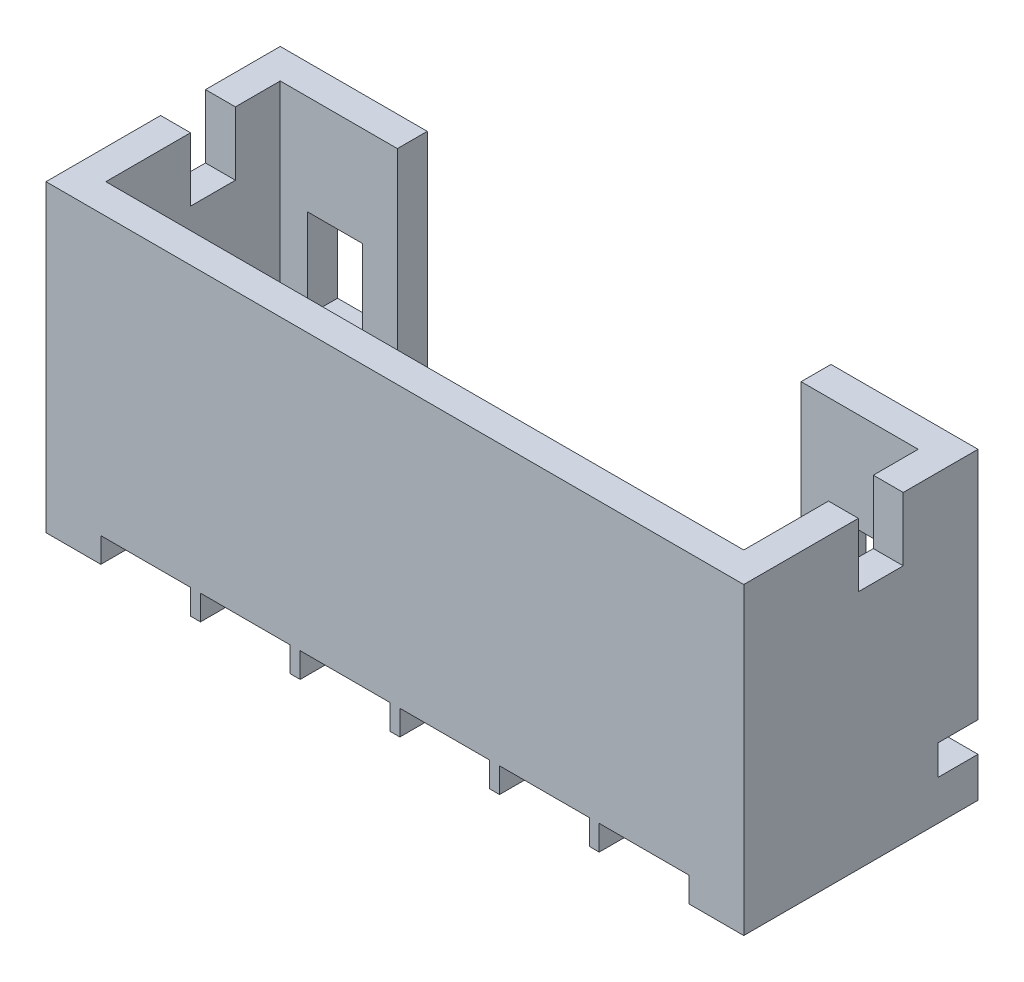
SolidWorks part; units mm, degrees
material "ABS"
ref_plane "Plano frontal" through (0, 0, 0) normal (0, 0, 1) x (1, 0, 0)
ref_plane "Plano superior" through (0, 0, 0) normal (0, 1, 0) x (1, 0, 0)
ref_plane "Plano direito" through (0, 0, 0) normal (1, 0, 0) x (0, 0, -1)
sketch "Esboço1" plane through (0, 0, 0) normal (0, 1, 0) x (1, 0, 0)
  line L1 (-7, -2.35) -> (7, -2.35)
  line L2 (-7, -2.35) -> (-7, 2.35)
  line L3 (-7, 2.35) -> (7, 2.35)
  line L4 (7, -2.35) -> (7, 2.35)
  line L5 (-7, -2.35) -> (7, 2.35) construction
  line L6 (-7, 2.35) -> (7, -2.35) construction
  point P0 (0, 0)
  dimension "D1" = 4.7
  dimension "D2" = 14
extrude "Ressalto-extrusão1" add sketch "Esboço1" along normal mid plane 6.1
shell "Casca1" thickness 0.6
sketch "Esboço2" plane through (0, 0, -2.35) normal (0, 0, -1) x (-1, 0, 0)
  line L0 (-4.05, 3.05) -> (-4.05, -1.35)
  line L1 (-7, 3.05) -> (7, 3.05) construction
  line L2 (-4.05, -1.35) -> (4.05, -1.35)
  line L3 (4.05, -1.35) -> (4.05, 3.05)
  line L4 (0, 0) -> (0, 2.0784) construction
  line L5 (0, 0) -> (1.8977, 0) construction
  line L7 (4.75, -0.75) -> (5.85, -0.75)
  line L8 (4.75, -0.75) -> (4.75, 1.05)
  line L9 (4.75, 1.05) -> (5.85, 1.05)
  line L10 (5.85, -0.75) -> (5.85, 1.05)
  line L11 (4.75, -0.75) -> (5.85, 1.05) construction
  line L12 (4.75, 1.05) -> (5.85, -0.75) construction
  line L13 (-5.85, 1.05) -> (-4.75, 1.05)
  line L14 (-5.85, 1.05) -> (-5.85, -0.75)
  line L15 (-5.85, -0.75) -> (-4.75, -0.75)
  line L16 (-4.75, 1.05) -> (-4.75, -0.75)
  line L17 (-5.85, 1.05) -> (-4.75, -0.75) construction
  line L18 (-5.85, -0.75) -> (-4.75, 1.05) construction
  line L19 (-7, 3.05) -> (-7, -3.05) construction
  line L20 (-4.05, 3.05) -> (4.05, 3.05)
  point P4 (0, -1.35)
  point P8 (5.3, 0.15)
  point P14 (-5.3, 0.15)
  dimension "D1" = 8.1
  dimension "D2" = 4.4
  dimension "D3" = 1.1
  dimension "D4" = 1.8
  dimension "D5" = 10.6
  dimension "D6" = 2
  dimension "D7" = 1.7
  dimension "D8" = 2
extrude "Corte-extrusão1" cut sketch "Esboço2" against normal blind 0.6 contours L20 L3 L2 L0 | L8 L7 L10 L9 | L14 L13 L16 L15
sketch "Esboço3" plane through (0, -2.45, 0) normal (0, 1, 0) x (1, 0, 0)
  line L4 (6.4, -1.75) -> (6.4, 1.75)
  line L5 (6.4, 1.75) -> (-6.4, 1.75)
  line L6 (-6.4, 1.75) -> (-6.4, -1.75)
  line L7 (-6.4, -1.75) -> (6.4, -1.75)
  line L8 (6.4, -1.75) -> (6.4, 1.75)
  line L9 (6.4, 1.75) -> (-6.4, 1.75)
  line L10 (-6.4, 1.75) -> (-6.4, -1.75)
  line L11 (-6.4, -1.75) -> (6.4, -1.75)
  dimension "D1" = 0
extrude "Ressalto-extrusão2" add sketch "Esboço3" along normal blind 1.1
sketch "Esboço4" plane through (0, 0, -2.35) normal (0, 0, -1) x (-1, 0, 0)
  line L0 (-7, 3.05) -> (-7, -3.05) construction
  line L1 (-7, -2.25) -> (7, -2.25)
  line L2 (-7, -2.25) -> (-7, -1.65)
  line L3 (-7, -1.65) -> (7, -1.65)
  line L4 (7, -2.25) -> (7, -1.65)
  line L5 (7, 3.05) -> (7, -3.05) construction
  line L6 (-7, -3.05) -> (7, -3.05) construction
  dimension "D1" = 0.8
  dimension "D2" = 0.6
extrude "Corte-extrusão2" cut sketch "Esboço4" against normal blind 0.8
sketch "Esboço5" plane through (7, 0, 0) normal (1, 0, 0) x (0, 0, -1)
  line L0 (-2.35, 3.05) -> (2.35, 3.05) construction
  line L1 (0.85, 3.05) -> (-0.05, 3.05)
  line L2 (0.85, 3.05) -> (0.85, 1.7749)
  line L3 (0.85, 1.7749) -> (-0.05, 1.7749)
  line L4 (-0.05, 3.05) -> (-0.05, 1.7749)
  line L5 (2.35, 3.05) -> (2.35, -1.65) construction
  dimension "D1" = 1.5
  dimension "D2" = 0.9
extrude "Corte-extrusão3" cut sketch "Esboço5" against normal through all both and the other way through all
sketch "Esboço8" plane through (0, -3.05, 0) normal (0, -1, 0) x (1, 0, 0)
  line L1 (0, -2.35) -> (0, 2.35) construction
  line L2 (-7, 2.35) -> (7, 2.35) construction
  line L5 (-2.75, -0.25) -> (-3.25, -0.25)
  line L6 (-4.75, 0.25) -> (-5.25, 0.25)
  line L7 (-4.75, 0.25) -> (-4.75, -0.25)
  line L8 (-4.75, -0.25) -> (-5.25, -0.25)
  line L9 (-5.25, 0.25) -> (-5.25, -0.25)
  line L10 (-4.75, 0.25) -> (-5.25, -0.25) construction
  line L11 (-4.75, -0.25) -> (-5.25, 0.25) construction
  line L12 (-2.75, 0.25) -> (-2.75, -0.25)
  line L13 (-2.75, 0.25) -> (-3.25, 0.25)
  line L14 (-3.25, 0.25) -> (-3.25, -0.25)
  line L15 (-0.75, -0.25) -> (-1.25, -0.25)
  line L16 (-0.75, 0.25) -> (-0.75, -0.25)
  line L17 (-0.75, 0.25) -> (-1.25, 0.25)
  line L18 (-1.25, 0.25) -> (-1.25, -0.25)
  line L19 (1.25, -0.25) -> (0.75, -0.25)
  line L20 (1.25, 0.25) -> (1.25, -0.25)
  line L21 (1.25, 0.25) -> (0.75, 0.25)
  line L22 (0.75, 0.25) -> (0.75, -0.25)
  line L23 (3.25, -0.25) -> (2.75, -0.25)
  line L24 (3.25, 0.25) -> (3.25, -0.25)
  line L25 (3.25, 0.25) -> (2.75, 0.25)
  line L26 (2.75, 0.25) -> (2.75, -0.25)
  line L27 (5.25, -0.25) -> (4.75, -0.25)
  line L28 (5.25, 0.25) -> (5.25, -0.25)
  line L29 (5.25, 0.25) -> (4.75, 0.25)
  line L30 (4.75, 0.25) -> (4.75, -0.25)
  point P0 (-1, -0.25)
  point P1 (1, 0.25)
  point P2 (1, -0.25)
  point P4 (0, 0)
  point P10 (0, 0)
  point P11 (3, -0.25)
  point P12 (3, 0.25)
  point P13 (5, 0.25)
  point P14 (-5, 0)
  point P19 (-1, 0.25)
  point P21 (-3, 0.25)
  point P41 (-3, -0.25)
  point P42 (-5, -0.25)
  dimension "D1" = 1
  dimension "D2" = 0.5
  dimension "D3" = 0.5
  dimension "D4" = 1
  dimension "D5" = 2
  dimension "D6" = 2
  dimension "D7" = 2
  dimension "D8" = 2
extrude "Corte-extrusão5" cut sketch "Esboço8" against normal through all
sketch "Esboço9" plane through (0, -3.05, 0) normal (0, -1, 0) x (1, 0, 0)
  line L0 (7, -2.35) -> (-7, -2.35) construction
  line L1 (-5.9, 2.3575) -> (-4.1, 2.3575)
  line L2 (-5.9, 2.3575) -> (-5.9, -2.35)
  line L3 (-5.9, -2.35) -> (-4.1, -2.35)
  line L4 (-4.1, 2.3575) -> (-4.1, -2.35)
  line L5 (-5.9, 2.3575) -> (-4.1, -2.35) construction
  line L6 (-5.9, -2.35) -> (-4.1, 2.3575) construction
  line L7 (-7, 2.35) -> (7, 2.35) construction
  line L8 (-3.9, 2.3575) -> (-2.1, 2.3575)
  line L9 (-3.9, 2.3575) -> (-3.9, -2.35)
  line L10 (-3.9, -2.35) -> (-2.1, -2.35)
  line L11 (-2.1, 2.3575) -> (-2.1, -2.35)
  line L12 (-3.9, 2.3575) -> (-2.1, -2.35) construction
  line L13 (-3.9, -2.35) -> (-2.1, 2.3575) construction
  line L14 (-1.9, 2.3575) -> (-0.1, 2.3575)
  line L15 (-1.9, 2.3575) -> (-1.9, -2.35)
  line L16 (-1.9, -2.35) -> (-0.1, -2.35)
  line L17 (-0.1, 2.3575) -> (-0.1, -2.35)
  line L18 (-1.9, 2.3575) -> (-0.1, -2.35) construction
  line L19 (-1.9, -2.35) -> (-0.1, 2.3575) construction
  line L20 (0.1, 2.3575) -> (1.9, 2.3575)
  line L21 (0.1, 2.3575) -> (0.1, -2.35)
  line L22 (0.1, -2.35) -> (1.9, -2.35)
  line L23 (1.9, 2.3575) -> (1.9, -2.35)
  line L24 (0.1, 2.3575) -> (1.9, -2.35) construction
  line L25 (0.1, -2.35) -> (1.9, 2.3575) construction
  line L26 (2.1, 2.3575) -> (3.9, 2.3575)
  line L27 (2.1, 2.3575) -> (2.1, -2.35)
  line L28 (2.1, -2.35) -> (3.9, -2.35)
  line L29 (3.9, 2.3575) -> (3.9, -2.35)
  line L30 (2.1, 2.3575) -> (3.9, -2.35) construction
  line L31 (2.1, -2.35) -> (3.9, 2.3575) construction
  line L32 (4.1, -2.3425) -> (5.9, -2.3425)
  line L33 (4.1, -2.3425) -> (4.1, 2.35)
  line L34 (4.1, 2.35) -> (5.9, 2.35)
  line L35 (5.9, -2.3425) -> (5.9, 2.35)
  line L36 (4.1, -2.3425) -> (5.9, 2.35) construction
  line L37 (4.1, 2.35) -> (5.9, -2.3425) construction
  point P0 (-5, 0.0038)
  point P7 (-3, 0.0038)
  point P12 (-1, 0.0038)
  point P17 (1, 0.0038)
  point P22 (3, 0.0038)
  point P27 (5, 0.0038)
  dimension "D1" = 1
  dimension "D2" = 1
  dimension "D3" = 2
  dimension "D4" = 2
  dimension "D5" = 2
  dimension "D6" = 2
  dimension "D7" = 1.8
extrude "Corte-extrusão6" cut sketch "Esboço9" against normal blind 0.5
sketch "Esboço10" plane through (0, 0, -2.3425) normal (0, 0, 1) x (1, 0, 0)
  line L4 (4.1, -3.05) -> (5.9, -3.05)
  line L5 (5.9, -3.05) -> (5.9, -2.55)
  line L6 (5.9, -2.55) -> (4.1, -2.55)
  line L7 (4.1, -2.55) -> (4.1, -3.05)
  line L8 (4.1, -3.05) -> (5.9, -3.05)
  line L9 (5.9, -3.05) -> (5.9, -2.55)
  line L10 (5.9, -2.55) -> (4.1, -2.55)
  line L11 (4.1, -2.55) -> (4.1, -3.05)
  dimension "D1" = 0
extrude "Corte-extrusão7" cut sketch "Esboço10" against normal through all
